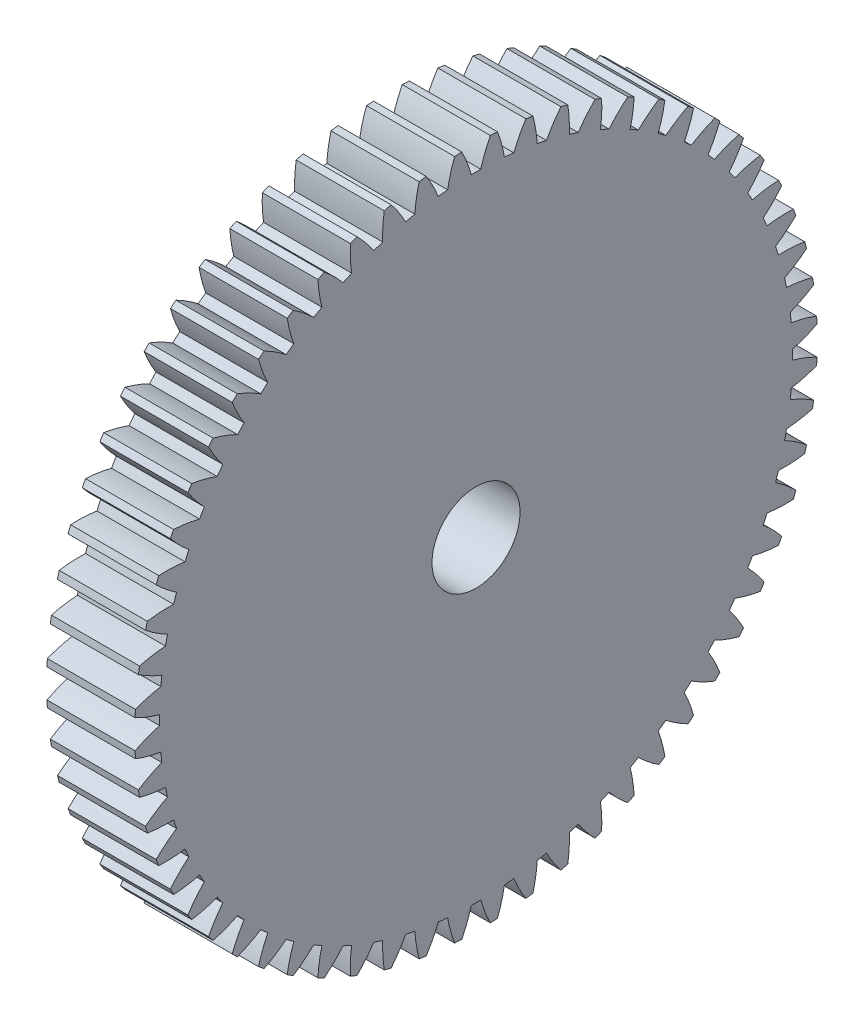
SolidWorks part; units mm, degrees
ref_plane "Plane1" through (0, 0, 0) normal (0, 0, 1) x (1, 0, 0)
ref_plane "Plane2" through (0, 0, 0) normal (0, 1, 0) x (1, 0, 0)
ref_plane "Plane3" through (0, 0, 0) normal (1, 0, 0) x (0, 0, -1)
other "Configuration Table"
sketch "HoldingSke" plane through (0, 0, 0) normal (0, 1, 0) x (1, 0, 0)
  line L0 (0, 0) -> (0.5, -0.866)
  line L1 (-15, 0) -> (100, 0) construction
  line L2 (0, 0) -> (-2.1039, 2.3779)
  line L3 (0, 0) -> (-11.863, 4.5341)
  line L4 (0, 0) -> (4.318, 7.479)
  line L5 (0, 0) -> (-46.8476, -17.4728)
  line L6 (0, 0) -> (-6.6317, -4.4744)
  line L7 (-2.1039, 2.3779) -> (8.6586, 51.2059)
  line L8 (-76.2, 54.61) -> (-74.8, 54.61)
  line L9 (-71.009, 38.7566) -> (-53.1078, 45.2721)
  line L10 (-76.2, 71.12) -> (104.1128, 71.12)
  line L11 (0, 0) -> (-8, 0)
  line L12 (-76.2, 101.6) -> (-76.162, 101.6)
  line L13 (24.9733, 27.94) -> (52.9518, 28.4284)
  line L14 (24.9733, 27.94) -> (24.9743, 27.94)
  line L15 (24.9733, 27.94) -> (100.4006, 29.5858)
  line L16 (-63.627, -1) -> (-12.827, -1)
  circle A0 centre (0, 0) radius 4
  circle A1 centre (0, 0) radius 28.749
  circle A2 centre (0, 0) radius 37.5
  circle A3 centre (0, 0) radius 4
  dimension "MHD" = 57.498
  dimension "Hub_dia" = 75
  dimension "Bore" = 8
  dimension "MBD" = 8
  dimension "Num_teeth" = 60
  dimension "Pitch" = 1
  dimension "Overall_len" = 50
  dimension "Show_teeth" = 60
  dimension "Thickness" = 8
  dimension "OAL" = 50.0001
  dimension "T_dim" = 1.4
  dimension "Ap" = 20
  dimension "H" = 19.05
  dimension "Pitch_radius" = 180.3128
  dimension "Width" = 8
  dimension "Backlash" = 0.038
  dimension "Addendum_fac" = 1
  dimension "Dedendum_fac" = 1.25
  dimension "Clearance_fac" = 0.25
  dimension "Dedendum_add" = 0.001
  dimension "Module" = 1
sketch "BasProSke" plane through (0, 0, 0) normal (0, 1, 0) x (1, 0, 0)
  line L0 (-10, 0) -> (60, 0) construction
  line L1 (0, 0) -> (0, 31)
  line L2 (0, 0) -> (8, 0)
  line L3 (8, 0) -> (8, 31)
  line L4 (8, 31) -> (0, 31)
  dimension "Thickness" = 8
  dimension "Diameter" = 62
revolve "Base-Revolve" add sketch "BasProSke" angle 360 about L0
sketch "TooCutSke" plane through (0, 0, 0) normal (1, 0, 0) x (0, 0, -1)
  line L1 (0, 0) -> (0, 107) construction
  line L2 (0, 0) -> (-0.8518, 29.9879) construction
  line L3 (0, 0) -> (-3.1393, 59.9006) construction
  line L4 (-0.8518, 29.9879) -> (-1.5696, 29.9503) construction
  arc A0 (0.4302, 28.7458) -> (-0.4302, 28.7458) centre (0, 0) ccw
  arc A1 (1.3127, 30.9976) -> (-1.3127, 30.9976) centre (0, 0) ccw
  circle A2 centre (0, 0) radius 30 construction
  circle A3 centre (0, 0) radius 28.1908 construction
  arc A4 (-0.4302, 28.7458) -> (-1.3127, 30.9976) centre (-11.9871, 25.5153) ccw
  arc A5 (1.3127, 30.9976) -> (0.4302, 28.7458) centre (11.9871, 25.5153) ccw
  dimension "Root_dia" = 57.498
  dimension "Overcut_dia" = 62.0508
  dimension "Pitch_dia" = 60
  dimension "Base_dia" = 56.3816
  dimension "Flank_rad" = 12
  dimension "Half_ang" = 3
  dimension "Half_CT" = 0.7188
extrude "ToothCut" cut sketch "TooCutSke" along normal through all
fillet "Breaks" [suppressed] radius 0.02
fillet "RootFillets" [suppressed] radius 0.251
pattern_circular "TeethCuts" count 60 every 6 about axis through (-10, 0, 0) along (1, 0, 0) of "ToothCut", "RootFillets", "Breaks"
sketch "HubNeaOneSke" plane through (0, 0, 0) normal (-1, 0, 0) x (0, 0, 1)
  circle A0 centre (0, 0) radius 28.749
  dimension "Diameter" = 57.498
extrude "HubNearOne" [suppressed] add sketch "HubNeaOneSke" along normal blind 42.0001
sketch "HubNeaBotSke" plane through (0, 0, 0) normal (-1, 0, 0) x (0, 0, 1)
  circle A0 centre (0, 0) radius 28.749
  dimension "Diameter" = 57.498
extrude "HubNearBoth" [suppressed] add sketch "HubNeaBotSke" along normal blind 21
ref_plane "FarPln" through (8, 0, 0) normal (1, 0, 0) x (0, 0, -1)
sketch "HubFarSke" plane through (8, 0, 0) normal (1, 0, 0) x (0, 0, -1)
  circle A0 centre (0, 0) radius 28.749
  dimension "Diameter" = 57.498
extrude "HubFar" [suppressed] add sketch "HubFarSke" along normal blind 21
sketch "BorSke" plane through (0, 0, 0) normal (1, 0, 0) x (0, 0, -1)
  circle A0 centre (0, 0) radius 4
  dimension "Diameter" = 8
extrude "Bore" cut sketch "BorSke" along normal mid plane 100.0001
sketch "KeySke" plane through (0, 0, 0) normal (1, 0, 0) x (0, 0, -1)
  line L0 (-1.5, 0) -> (-1.5, 5.4)
  line L1 (-1.5, 5.4) -> (1.5, 5.4)
  line L2 (1.5, 5.4) -> (1.5, 0)
  line L3 (0, 0) -> (0, 34) construction
  line L4 (-1.5, 0) -> (1.5, 0)
  dimension "Offset" = 5.4
  dimension "Width" = 3
extrude "Keyway" [suppressed] cut sketch "KeySke" along normal mid plane 100.0001
pattern_circular "Keyway2" [suppressed] count 2 every 90 about axis through (-10, 0, 0) along (1, 0, 0)
equation "' \"Module@HoldingSke\" = 6.35"
equation "' \"Num_teeth@HoldingSke\" = 12"
equation "' \"Ap@HoldingSke\" =  20"
equation "' \"Ap@HoldingSke\" = 20"
equation "' \"Width@HoldingSke\" = 0.5 * 25.4"
equation "' \"Hub_dia@HoldingSke\"= 1 * 25.4"
equation "' \"Hub_dia@HoldingSke\" = 1 * 25.4"
equation "' \"Overall_len@HoldingSke\" = 1.0 * 25.4"
equation "' \"Bore@HoldingSke\" = 0.75 * 25.4"
equation "' \"T_dim@HoldingSke\" = 0.1 * 25.4"
equation "' \"Width@KeySke\" = 0.25 * 25.4"
equation "' \"Show_teeth@HoldingSke\" = 13"
equation "' \"Backlash@HoldingSke\" = 0.009 * 25.4"
equation "' \"Addendum_fac@HoldingSke\" = 1.0"
equation "' \"Dedendum_fac@HoldingSke\" = 1.25"
equation "' \"Dedendum_add@HoldingSke\" = 0.00005 * 25.4"
equation "' \"Clearance_fac@HoldingSke\" = 0.25"
equation "\"Pitch@HoldingSke\" = 1 / \"Module@HoldingSke\""
equation "\"Overcut_dia@TooCutSke\" = (\"Num_teeth@HoldingSke\" + 2 * \"Addendum_fac@HoldingSke\") / \"Pitch@HoldingSke\" + 0.002 * 25.4"
equation "\"Pitch_dia@TooCutSke\" = \"Num_teeth@HoldingSke\" / \"Pitch@HoldingSke\""
equation "\"Base_dia@TooCutSke\" = \"Num_teeth@HoldingSke\" / \"Pitch@HoldingSke\" * cos((\"Ap@HoldingSke\"  * 3.14159265 / 180))"
equation "\"Root_dia@TooCutSke\" = (\"Num_teeth@HoldingSke\" + 2) / \"Pitch@HoldingSke\" - 2 * (\"Addendum_fac@HoldingSke\" + \"Dedendum_fac@HoldingSke\") / \"Pitch@HoldingSke\" - \"Dedendum_add@HoldingSke\" * 2"
equation "\"Half_ang@TooCutSke\" = 180 / \"Num_teeth@HoldingSke\""
equation "\"Half_CT@TooCutSke\" = \"Num_teeth@HoldingSke\" / \"Pitch@HoldingSke\" * sin((3.14159265 / 2 / \"Num_teeth@HoldingSke\")) / 2 - 7 * \"Backlash@HoldingSke\" / 4"
equation "\"Flank_rad@TooCutSke\" = \"Num_teeth@HoldingSke\" / \"Pitch@HoldingSke\" / 5"
equation "\"Radius@RootFillets\" = \"Clearance_fac@HoldingSke\" / \"Pitch@HoldingSke\" + \"Dedendum_add@HoldingSke\""
equation "\"Break_rad@Breaks\" = 0.02 / \"Pitch@HoldingSke\""
equation "\"Thickness@HoldingSke\" = \"Width@HoldingSke\""
equation "\"OAL@HoldingSke\" = \"Thickness@HoldingSke\""
equation "\"MHD@HoldingSke\" = (\"Num_teeth@HoldingSke\" + 2) / \"Pitch@HoldingSke\" - 2 * (\"Addendum_fac@HoldingSke\" + \"Dedendum_fac@HoldingSke\")  / \"Pitch@HoldingSke\" - \"Dedendum_add@HoldingSke\" * 2"
equation "\"MBD@HoldingSke\" = (\"Num_teeth@HoldingSke\" + 2) / \"Pitch@HoldingSke\" - 2 * (\"Addendum_fac@HoldingSke\" + \"Dedendum_fac@HoldingSke\")  / \"Pitch@HoldingSke\" - \"Dedendum_add@HoldingSke\" * 2 - 0.002 * 25.4"
equation "\"MHD@HoldingSke\" = ((sgn( \"MHD@HoldingSke\" - \"Hub_dia@HoldingSke\" )-1)*( \"MHD@HoldingSke\" - \"Hub_dia@HoldingSke\" ))/-2+ \"Hub_dia@HoldingSke\""
equation "\"MBD@HoldingSke\" = ((sgn( \"MBD@HoldingSke\" - \"Bore@HoldingSke\" )-1)*( \"MBD@HoldingSke\" - \"Bore@HoldingSke\" ))/-2+ \"Bore@HoldingSke\""
equation "\"OAL@HoldingSke\" = ((sgn( \"OAL@HoldingSke\" - \"Overall_len@HoldingSke\" )+1)*( \"OAL@HoldingSke\" - \"Overall_len@HoldingSke\" ))/2 + \"Overall_len@HoldingSke\" + 0.000002 * 25.4"
equation "\"Num_teeth@TeethCuts\" = int( \"Show_teeth@HoldingSke\" ) + 1"
equation "\"Num_teeth@TeethCuts\" = ((sgn( \"Num_teeth@TeethCuts\" - \"Num_teeth@HoldingSke\" )-1)*( \"Num_teeth@TeethCuts\" - \"Num_teeth@HoldingSke\" ))/-2+ \"Num_teeth@HoldingSke\""
equation "\"Num_teeth@TeethCuts\" = ((sgn( \"Num_teeth@TeethCuts\" - 2.0)+1)*( \"Num_teeth@TeethCuts\" - 2.0))/2 +2.0"
equation "\"Angle@TeethCuts\" = 360.0 / \"Num_teeth@HoldingSke\""
equation "\"Diameter@BasProSke\" = (\"Num_teeth@HoldingSke\" + 2 * \"Addendum_fac@HoldingSke\") / \"Pitch@HoldingSke\""
equation "\"Thickness@BasProSke\"  = \"Thickness@HoldingSke\""
equation "' \"Fillet_rad@BasProSke\" =  \"Thickness@HoldingSke\" * 0.05"
equation "' \"Fillet_rad@BasProSke\" = \"Thickness@HoldingSke\" * 0.05"
equation "\"MHD@HoldingSke\" = ((sgn( \"MHD@HoldingSke\" - \"Root_dia@TooCutSke\" )-1)*( \"MHD@HoldingSke\" - \"Root_dia@TooCutSke\" ))/-2+ \"Root_dia@TooCutSke\""
equation "\"Diameter@HubNeaOneSke\" = \"MHD@HoldingSke\""
equation "\"Length@HubNearOne\" = \"OAL@HoldingSke\" - \"Thickness@BasProSke\""
equation "\"Diameter@HubNeaBotSke\" = \"MHD@HoldingSke\""
equation "\"Length@HubNearBoth\" = ( \"OAL@HoldingSke\" - \"Thickness@BasProSke\" ) / 2.0"
equation "\"Thickness@FarPln\" = \"Thickness@BasProSke\""
equation "\"Diameter@HubFarSke\" = \"MHD@HoldingSke\""
equation "\"Length@HubFar\" = ( \"OAL@HoldingSke\" - \"Thickness@BasProSke\" ) / 2.0"
equation "\"Diameter@BorSke\" = \"MBD@HoldingSke\""
equation "\"D1@Bore\" = \"OAL@HoldingSke\" * 2.0"
equation "\"D1@Keyway\" = \"OAL@HoldingSke\" * 2.0"
equation "\"Offset@KeySke\" = \"T_dim@HoldingSke\" + \"MBD@HoldingSke\" / 2.0"
